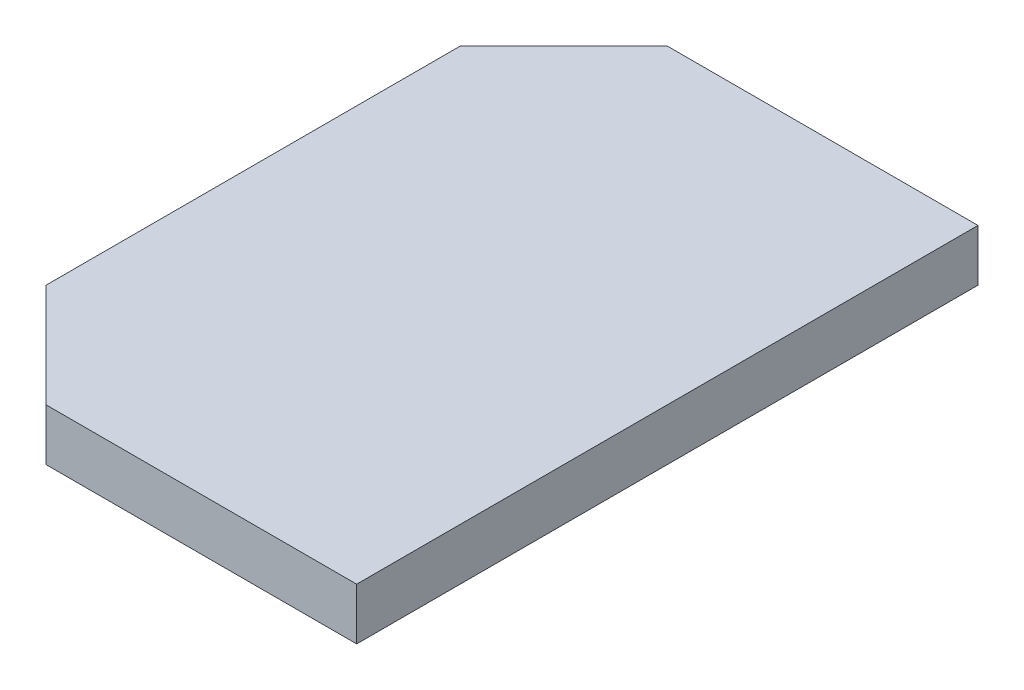
SolidWorks part; units mm, degrees
material "6061-O (SS)"
ref_plane "Front Plane" through (0, 0, 0) normal (0, 0, 1) x (1, 0, 0)
ref_plane "Top Plane" through (0, 0, 0) normal (0, 1, 0) x (1, 0, 0)
ref_plane "Right Plane" through (0, 0, 0) normal (1, 0, 0) x (0, 0, -1)
sketch "Sketch1" plane through (0, 0, 0) normal (0, 1, 0) x (1, 0, 0)
  line L0 (-25.4, 25.4) -> (-12.7, 38.1)
  line L1 (25.4, 38.1) -> (-25.4, 38.1)
  line L2 (25.4, 38.1) -> (25.4, -38.1)
  line L3 (25.4, -38.1) -> (-25.4, -38.1)
  line L4 (-25.4, 38.1) -> (-25.4, -38.1)
  line L5 (25.4, 38.1) -> (-25.4, -38.1) construction
  line L6 (25.4, -38.1) -> (-25.4, 38.1) construction
  line L7 (-25.4, -25.4) -> (-12.7, -38.1)
  point P0 (0, 0)
  dimension "D1" = 50.8
  dimension "D2" = 76.2
  dimension "D3" = 12.7
  dimension "D4" = 12.7
  dimension "D5" = 12.7
  dimension "D6" = 12.7
extrude "Boss-Extrude1" add sketch "Sketch1" along normal mid plane 6.35 contours L4 L7 L3 L2 L1 L0
